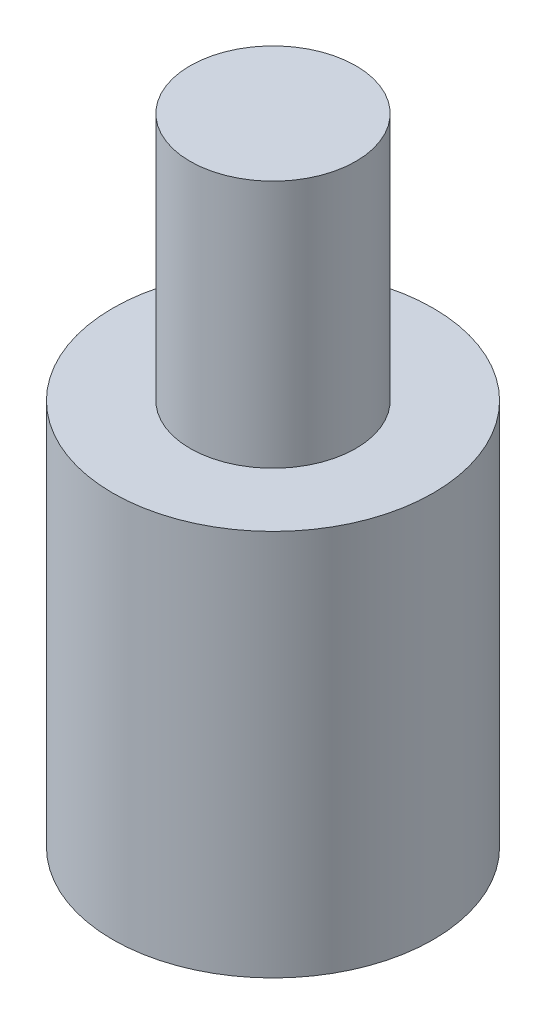
SolidWorks part; units mm, degrees
ref_plane "Front Plane" through (0, 0, 0) normal (0, 0, 1) x (1, 0, 0)
ref_plane "Top Plane" through (0, 0, 0) normal (0, 1, 0) x (1, 0, 0)
ref_plane "Right Plane" through (0, 0, 0) normal (1, 0, 0) x (0, 0, -1)
sketch "OD_base" plane through (0, 0, 0) normal (0, 1, 0) x (1, 0, 0)
  circle A0 centre (0, 0) radius 2.9
  dimension "D1" = 5.8
extrude "standoff_base" add sketch "OD_base" along normal blind 7
sketch "OD_post_mount" plane through (0, 7, 0) normal (0, 1, 0) x (1, 0, 0)
  circle A0 centre (0, 0) radius 1.5
  dimension "D1" = 3
extrude "standoff_post" add sketch "OD_post_mount" along normal blind 4.5
cosmetic thread "m3x0.5_threads_1" parameters "D2"=2.439
sketch "ID_post_mount" plane through (0, 0, 0) normal (0, -1, 0) x (1, 0, 0)
  circle A0 centre (0, 0) radius 1.2195
  dimension "D1" = 2.439
extrude "post_mount" cut sketch "ID_post_mount" against normal blind 3 contours A0
cosmetic thread "m3x0.5_threads_2" parameters "D1"=2.9999, "D2"=3
sketch "Sketch4" plane through (0, 0, 0) normal (0, -1, 0) x (1, 0, 0)
  circle A3 centre (0, 0) radius 1.7195
  circle A4 centre (0, 0) radius 1.7195
  dimension "D1" = 0.5
split line "brass_insert"
equation "\"D1@ID_post_mount\"=\"D2@m3x0.5_threads_1\""
